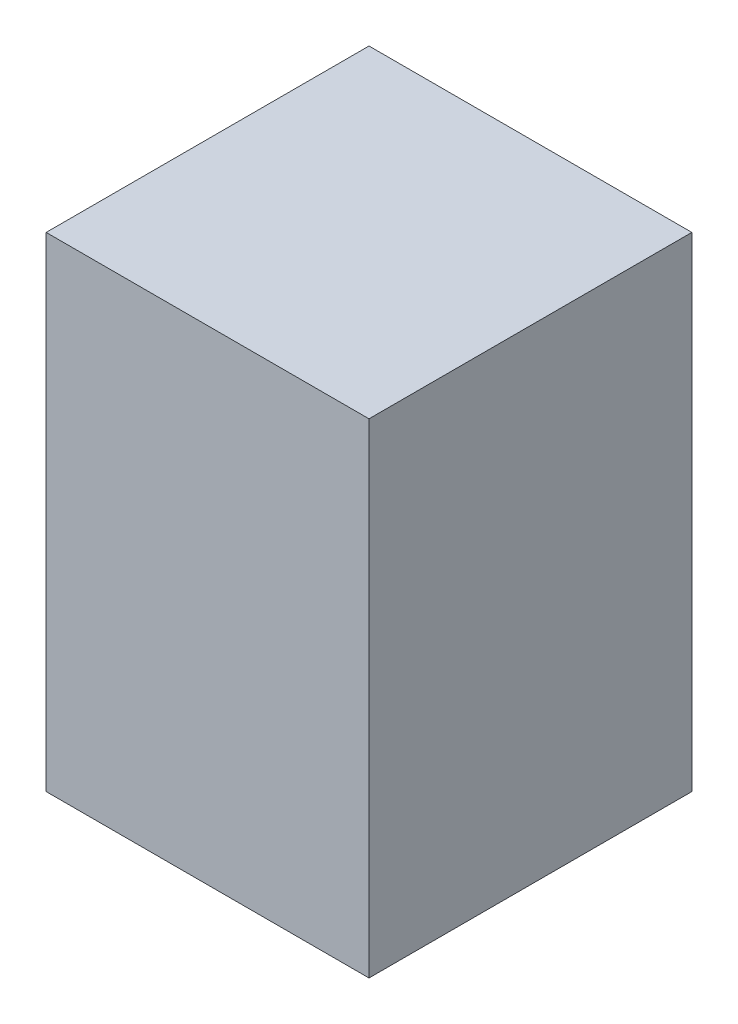
SolidWorks part; units mm, degrees
ref_plane "Front" through (0, 0, 0) normal (0, 0, 1) x (1, 0, 0)
ref_plane "Top" through (0, 0, 0) normal (0, 1, 0) x (1, 0, 0)
ref_plane "Right" through (0, 0, 0) normal (1, 0, 0) x (0, 0, -1)
sketch "Sketch1" plane through (0, 0, 0) normal (0, 1, 0) x (1, 0, 0)
  line L1 (-76.2, -76.2) -> (76.2, -76.2)
  line L2 (-76.2, -76.2) -> (-76.2, 76.2)
  line L3 (-76.2, 76.2) -> (76.2, 76.2)
  line L4 (76.2, -76.2) -> (76.2, 76.2)
  line L5 (-76.2, -76.2) -> (76.2, 76.2) construction
  line L6 (-76.2, 76.2) -> (76.2, -76.2) construction
  point P0 (0, 0)
  dimension "D1" = 152.4
  dimension "D2" = 152.4
extrude "Boss-Extrude1" add sketch "Sketch1" along normal blind 228.6
